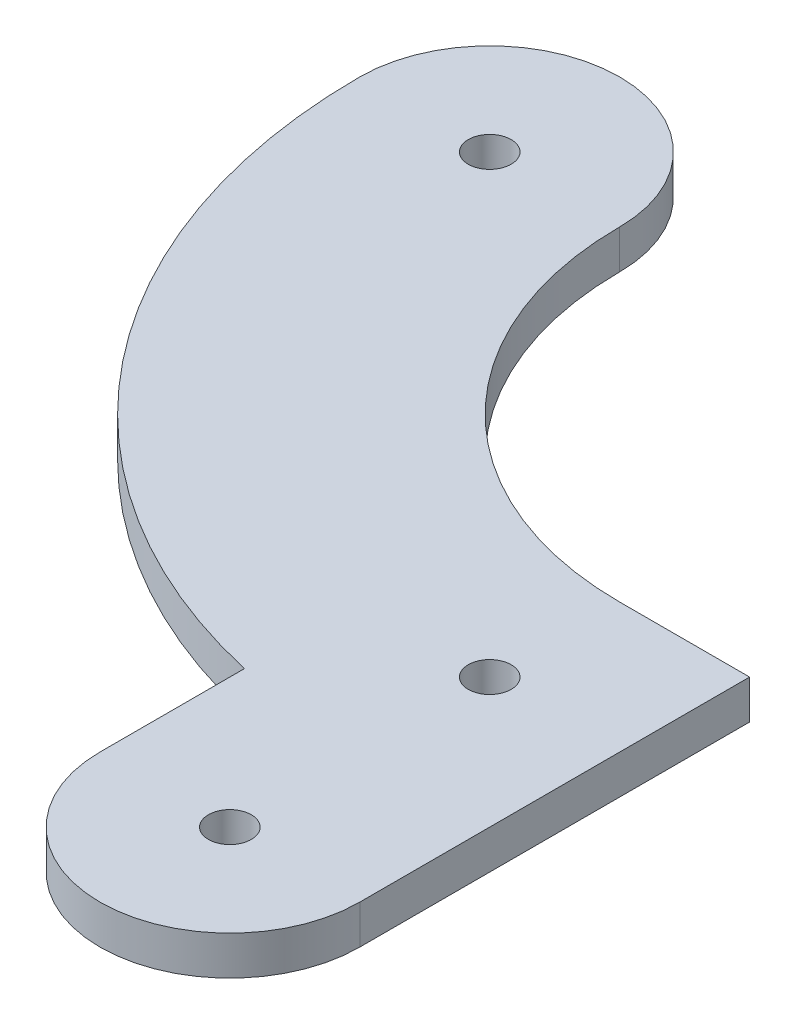
SolidWorks part; units mm, degrees
material "Thornel Mat VMA"
ref_plane "前视基准面" through (0, 0, 0) normal (0, 0, 1) x (1, 0, 0)
ref_plane "上视基准面" through (0, 0, 0) normal (0, 1, 0) x (1, 0, 0)
ref_plane "右视基准面" through (0, 0, 0) normal (1, 0, 0) x (0, 0, -1)
sketch "草图1" plane through (0, 0, 0) normal (0, 1, 0) x (1, 0, 0)
  line L0 (0, 0) -> (0, 20) construction
  line L1 (10, 0) -> (10, 30)
  line L2 (-10, 0) -> (-10, 11.1252)
  line L3 (0, 30) -> (10, 30)
  line L4 (10, 0) -> (10, 32.0871) construction
  arc A0 (0, 20) -> (-35, 55) centre (0, 55) cw construction
  arc A1 (0, 30) -> (-25, 55) centre (0, 55) cw
  arc A2 (-10, 11.1252) -> (-45, 55) centre (0, 55) cw
  arc A3 (10, 0) -> (-10, 0) centre (0, 0) cw
  arc A4 (-25, 55) -> (-45, 55) centre (-35, 55) ccw
  arc A5 (10, 32.0871) -> (-25, 55) centre (0, 55) cw construction
  circle A6 centre (-35, 55) radius 1.65
  circle A7 centre (0, 20) radius 1.65
  circle A8 centre (0, 0) radius 1.65
  dimension "D3" = 35
  dimension "D5" = 20
  dimension "D6" = 3.3
  dimension "D7" = 3.3
  dimension "D8" = 3.3
  dimension "D4" = 20
  dimension "D1" = 10
  dimension "D2" = 10
extrude "凸台-拉伸1" add sketch "草图1" along normal blind 3
